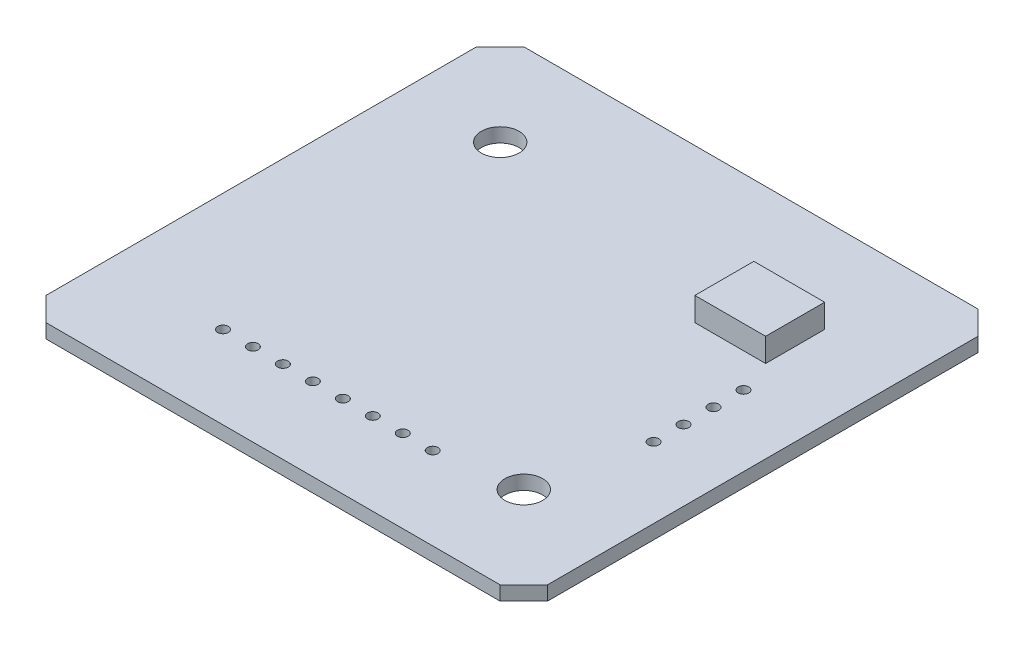
SolidWorks part; units mm, degrees
ref_plane "前视基准面" through (0, 0, 0) normal (0, 0, 1) x (1, 0, 0)
ref_plane "上视基准面" through (0, 0, 0) normal (0, 1, 0) x (1, 0, 0)
ref_plane "右视基准面" through (0, 0, 0) normal (1, 0, 0) x (0, 0, -1)
other "Configuration Table"
sketch "草图1" plane through (0, 0, 0) normal (0, 1, 0) x (1, 0, 0)
  line L0 (19.25, -20.25) -> (21.25, -18.25)
  line L1 (-19.25, 20.25) -> (19.25, 20.25)
  line L2 (-21.25, 18.25) -> (-21.25, -18.25)
  line L3 (-19.25, -20.25) -> (19.25, -20.25)
  line L4 (21.25, 18.25) -> (21.25, -18.25)
  line L5 (-21.25, 20.25) -> (21.25, -20.25) construction
  line L6 (-21.25, -20.25) -> (21.25, 20.25) construction
  line L7 (21.25, -0.8163) -> (21.25, -50000.8163) construction
  line L8 (6.6805, 20.25) -> (-49993.3195, 20.25) construction
  line L9 (-21.25, 3.5616) -> (-21.25, -49996.4384) construction
  line L10 (7.1955, -20.25) -> (-49992.8045, -20.25) construction
  line L11 (-21.25, -18.25) -> (-19.25, -20.25)
  line L12 (-19.25, 20.25) -> (-21.25, 18.25)
  line L13 (19.25, 20.25) -> (21.25, 18.25)
  circle A0 centre (13.25, -12.25) radius 1.6
  circle A1 centre (-13.25, 12.25) radius 1.6
  circle A2 centre (-11.25, -13.25) radius 0.45
  circle A3 centre (-8.71, -13.25) radius 0.45
  circle A4 centre (-6.17, -13.25) radius 0.45
  circle A5 centre (-3.63, -13.25) radius 0.45
  circle A6 centre (-1.09, -13.25) radius 0.45
  circle A7 centre (1.45, -13.25) radius 0.45
  circle A8 centre (3.99, -13.25) radius 0.45
  circle A9 centre (6.53, -13.25) radius 0.45
  circle A10 centre (15.25, -3.25) radius 0.45
  circle A11 centre (15.25, -0.71) radius 0.45
  circle A12 centre (15.25, 1.83) radius 0.45
  circle A13 centre (15.25, 4.37) radius 0.45
  point P0 (0, 0)
  dimension "D11" = 3.2
  dimension "D12" = 3.2
  dimension "D18" = 0.9
  dimension "D20" = 0.9
  dimension "D1" = 40.5
  dimension "D2" = 42.5
  dimension "D3" = 2
  dimension "D4" = 2
  dimension "D5" = 2
  dimension "D6" = 2
  dimension "D7" = 2
  dimension "D8" = 2
  dimension "D9" = 2
  dimension "D10" = 2
  dimension "D13" = 8
  dimension "D14" = 8
  dimension "D15" = 8
  dimension "D16" = 10
  dimension "D17" = 7
  dimension "D21" = 6
  dimension "D22" = 17
  dimension "D19" = 8
  dimension "D23" = 4
extrude "凸台-拉伸1" add sketch "草图1" along normal blind 1.2
sketch "草图3" plane through (0, 1.2, 0) normal (0, 1, 0) x (1, 0, 0)
  line L0 (21.25, -18.25) -> (21.25, 18.25) construction
  line L1 (8.25, 12.25) -> (14.25, 12.25)
  line L2 (8.25, 12.25) -> (8.25, 7.25)
  line L3 (8.25, 7.25) -> (14.25, 7.25)
  line L4 (14.25, 12.25) -> (14.25, 7.25)
  line L5 (19.25, 20.25) -> (-19.25, 20.25) construction
  dimension "D1" = 7
  dimension "D2" = 8
  dimension "D3" = 5
  dimension "D4" = 6
extrude "凸台-拉伸2" add sketch "草图3" along normal blind 2
